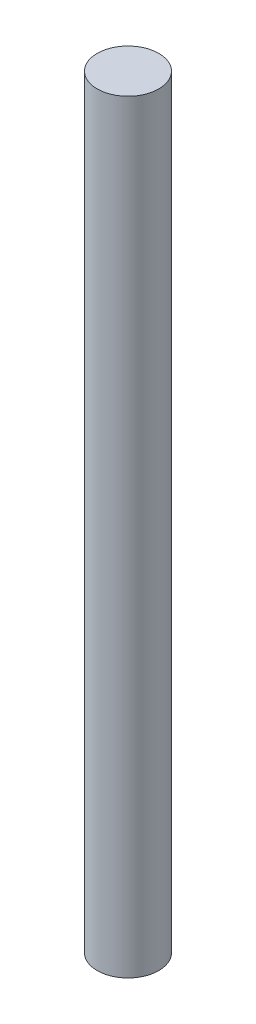
SolidWorks part; units mm, degrees
ref_plane "Front Plane" through (0, 0, 0) normal (0, 0, 1) x (1, 0, 0)
ref_plane "Top Plane" through (0, 0, 0) normal (0, 1, 0) x (1, 0, 0)
ref_plane "Right Plane" through (0, 0, 0) normal (1, 0, 0) x (0, 0, -1)
sketch "Sketch1" plane through (0, 0, 0) normal (0, 1, 0) x (1, 0, 0)
  circle A0 centre (0, 0) radius 2.5
  dimension "D1" = 5
extrude "Boss-Extrude1" add sketch "Sketch1" along normal blind 72
sketch "Sketch3" plane through (0, 72, 0) normal (0, 1, 0) x (1, 0, 0)
  circle A0 centre (0, 0) radius 2.5
extrude "Cut-Extrude1" cut sketch "Sketch3" against normal blind 10
